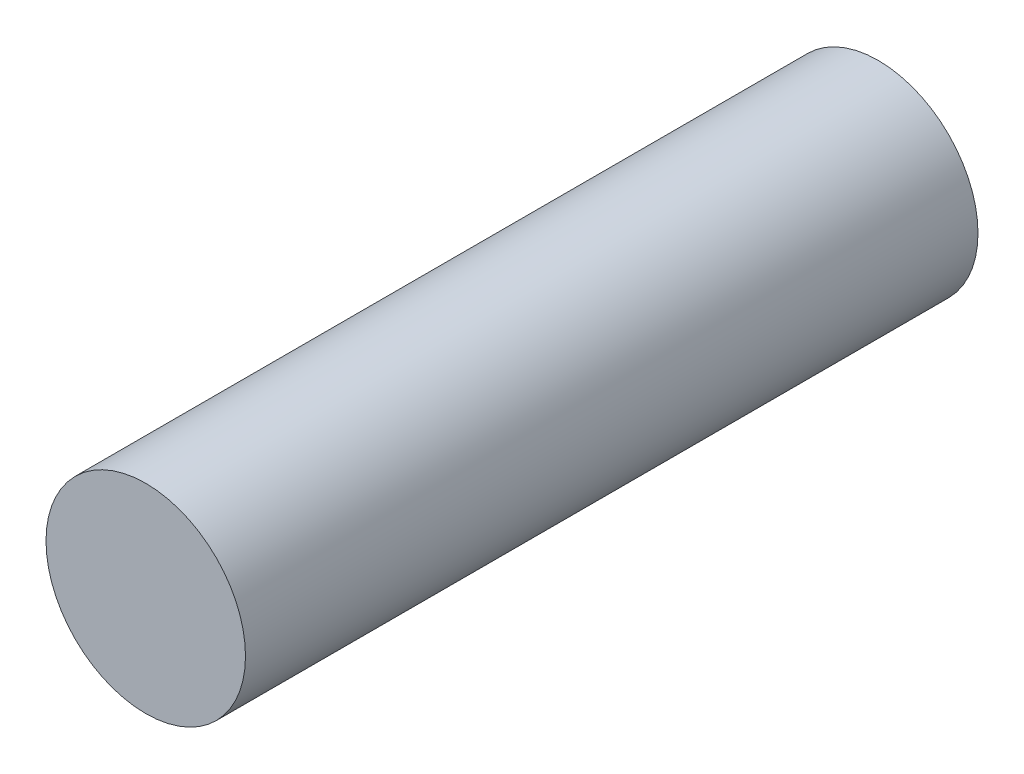
SolidWorks part; units mm, degrees
ref_plane "Front Plane" through (0, 0, 0) normal (0, 0, 1) x (1, 0, 0)
ref_plane "Top Plane" through (0, 0, 0) normal (0, 1, 0) x (1, 0, 0)
ref_plane "Right Plane" through (0, 0, 0) normal (1, 0, 0) x (0, 0, -1)
sketch "Sketch1" plane through (0, 0, 0) normal (0, 0, 1) x (1, 0, 0)
  circle A0 centre (0, 0) radius 3.2
  dimension "D1" = 6.4
extrude "Boss-Extrude1" add sketch "Sketch1" along normal blind 23.5
scale "缩放比例1" scale about centroid uniform scaling yes scale factor 2
